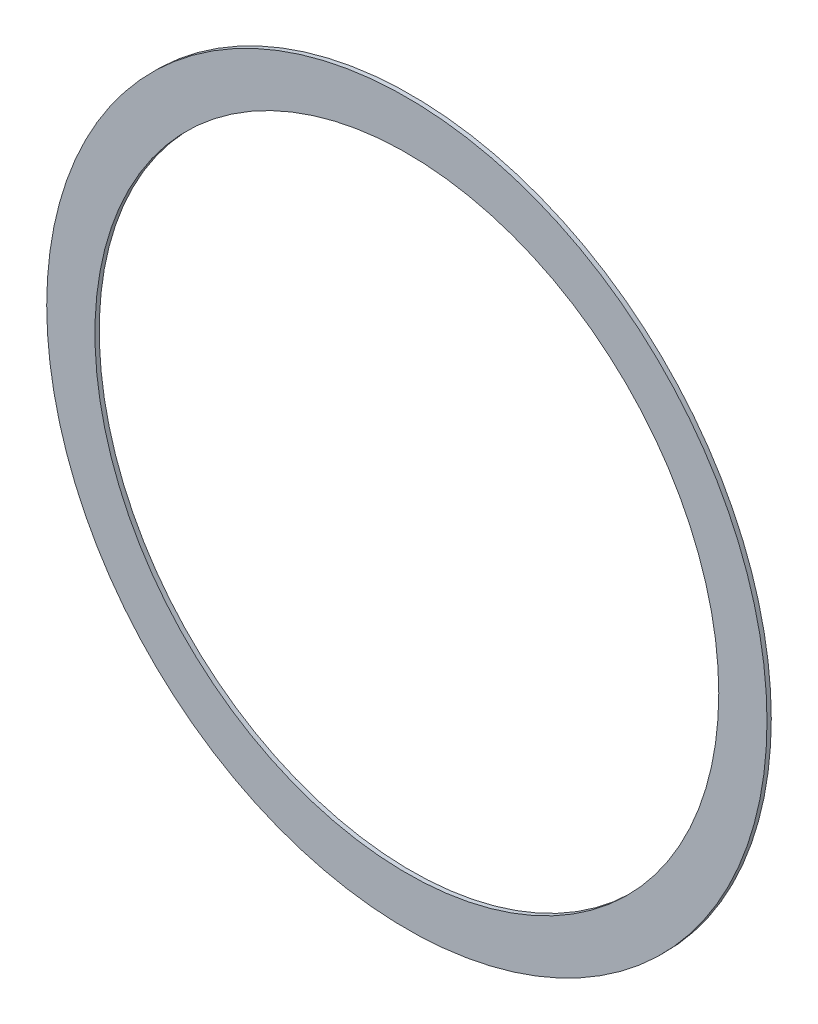
SolidWorks part; units mm, degrees
material "Rubber"
ref_plane "Front Plane" through (0, 0, 0) normal (0, 0, 1) x (1, 0, 0)
ref_plane "Top Plane" through (0, 0, 0) normal (0, 1, 0) x (1, 0, 0)
ref_plane "Right Plane" through (0, 0, 0) normal (1, 0, 0) x (0, 0, -1)
sketch "Sketch1" plane through (0, 0, 0) normal (0, 0, 1) x (1, 0, 0)
  circle A0 centre (0, 0) radius 230.9812
  circle A1 centre (0, 0) radius 266.7
  dimension "D1" = 461.9625
  dimension "D2" = 533.4
extrude "Boss-Extrude1" add sketch "Sketch1" along normal blind 3.175
